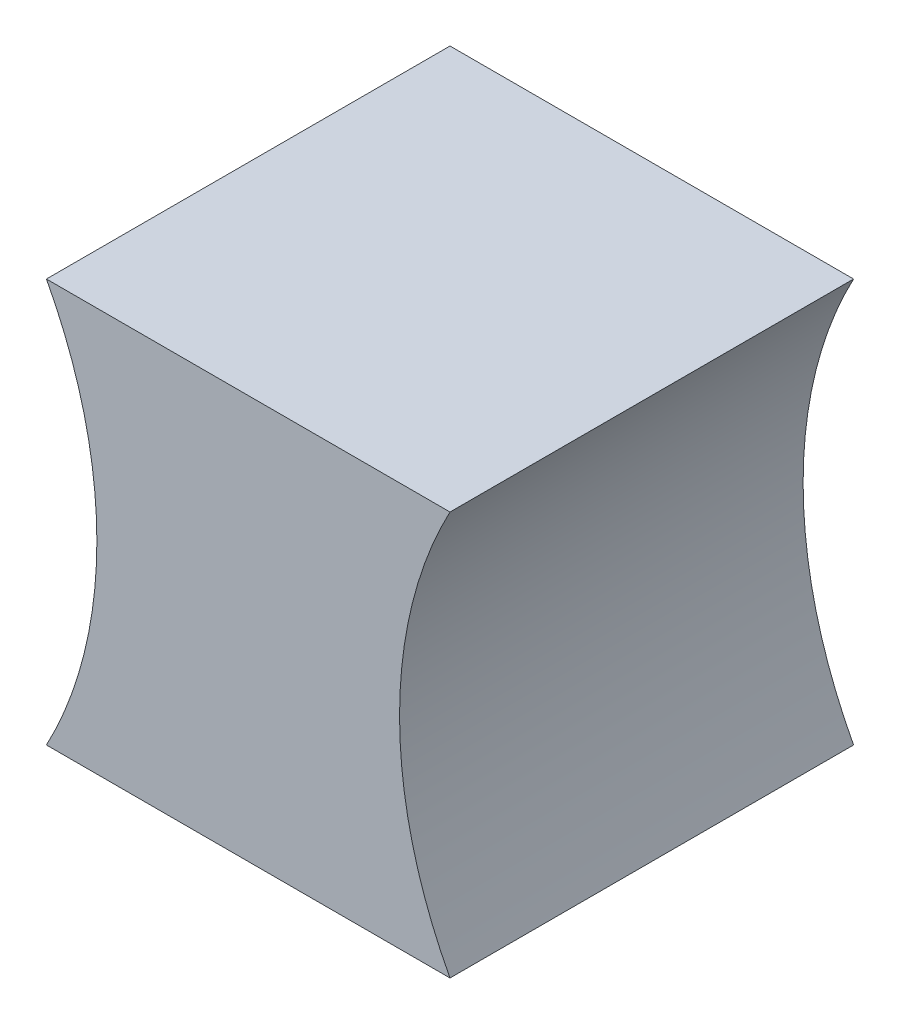
SolidWorks part; units mm, degrees
ref_plane "Front Plane" through (0, 0, 0) normal (0, 0, 1) x (1, 0, 0)
ref_plane "Top Plane" through (0, 0, 0) normal (0, 1, 0) x (1, 0, 0)
ref_plane "Right Plane" through (0, 0, 0) normal (1, 0, 0) x (0, 0, -1)
sketch "Sketch1" plane through (0, 0, 0) normal (0, 0, 1) x (1, 0, 0)
  line L0 (0, 0) -> (1000, 0)
  line L1 (0, 0) -> (0, 1163.3903) construction
  line L2 (1000, 0) -> (1000, 1163.3903) construction
  line L3 (0, 1000) -> (1000, 1000)
  arc A0 (0, 0) -> (0, 1000) centre (-937.5, 500) ccw
  arc A1 (1000, 0) -> (1000, 1000) centre (1937.5, 500) cw
  dimension "D4" = 250
  dimension "D3" = 1000
  dimension "D2" = 250
  dimension "D1" = 1000
  dimension "D5" = 1000
extrude "Boss-Extrude1" add sketch "Sketch1" along normal blind 1000
